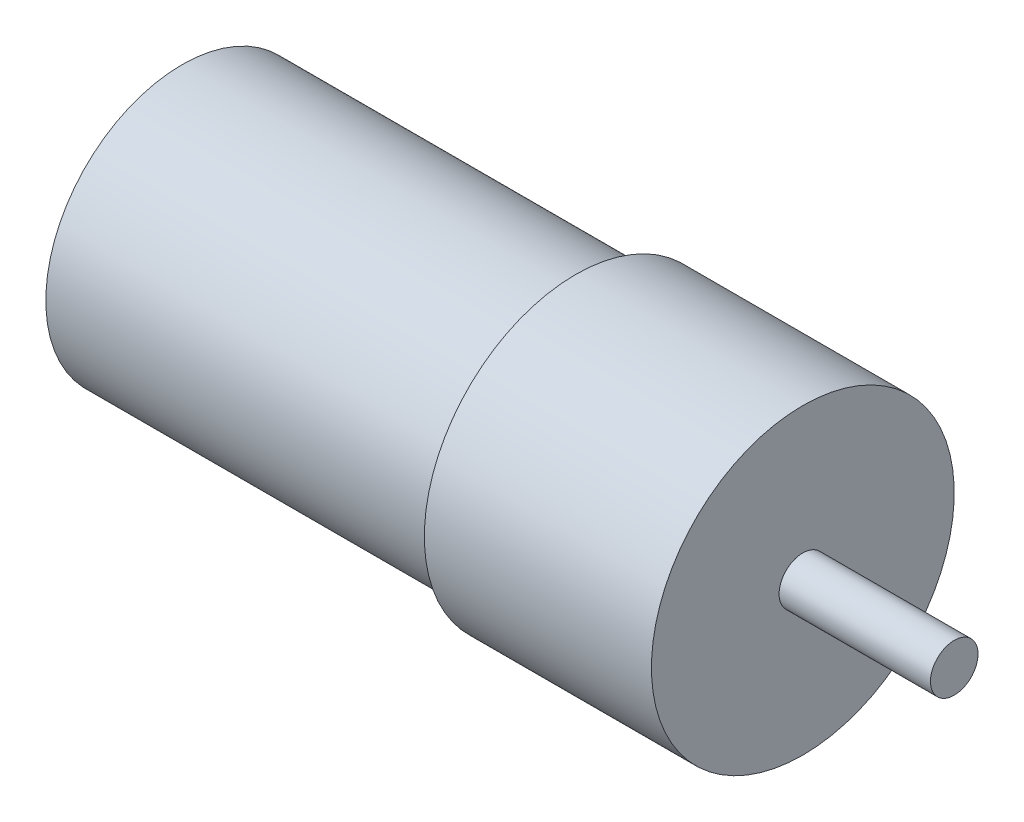
SolidWorks part; units mm, degrees
ref_plane "Front Plane" through (0, 0, 0) normal (0, 0, 1) x (1, 0, 0)
ref_plane "Top Plane" through (0, 0, 0) normal (0, 1, 0) x (1, 0, 0)
ref_plane "Right Plane" through (0, 0, 0) normal (1, 0, 0) x (0, 0, -1)
sketch "Sketch1" plane through (0, 0, 0) normal (0, 0, 1) x (1, 0, 0)
  line L0 (0, 0) -> (0, 1.9939)
  line L1 (0, 1.9939) -> (-12.7, 1.9939)
  line L2 (-12.7, 1.9939) -> (-12.7, 12.7)
  line L3 (-12.7, 12.7) -> (-31.75, 12.7)
  line L4 (-31.75, 12.7) -> (-31.75, 11.43)
  line L5 (-31.75, 11.43) -> (-64.77, 11.43)
  line L6 (-64.77, 11.43) -> (-64.77, 0)
  line L7 (-64.77, 0) -> (0, 0)
  dimension "D1" = 11.43
  dimension "D2" = 12.7
  dimension "D3" = 1.9939
  dimension "D4" = 12.7
  dimension "D5" = 19.05
  dimension "D6" = 33.02
revolve "Revolve1" add sketch "Sketch1" angle 360 about L7
